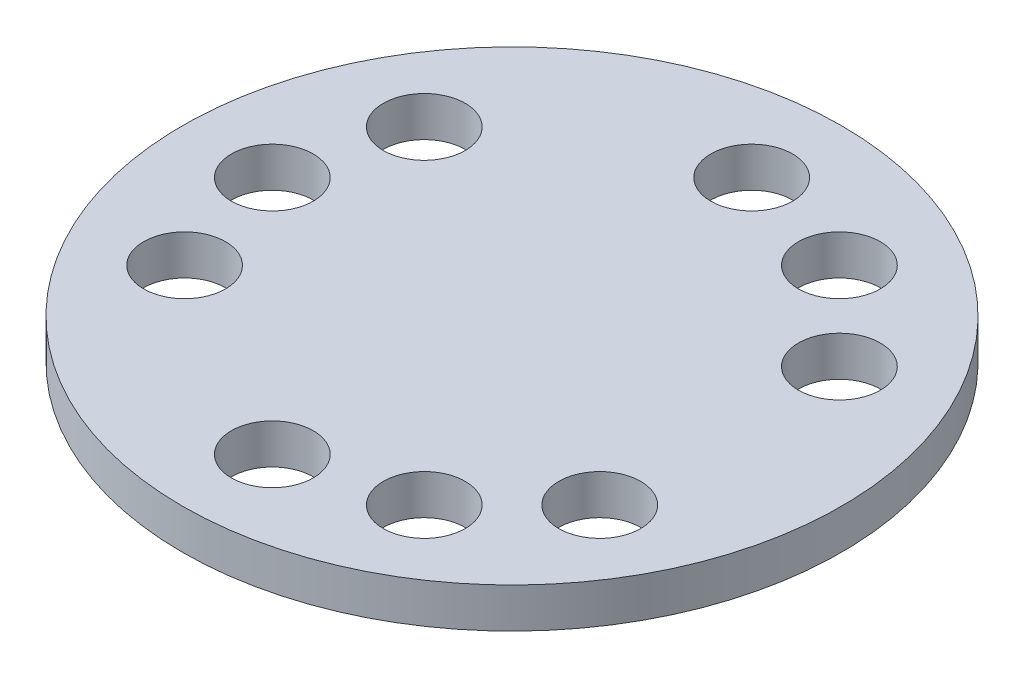
SolidWorks part; units mm, degrees
ref_plane "前视基准面" through (0, 0, 0) normal (0, 0, 1) x (1, 0, 0)
ref_plane "上视基准面" through (0, 0, 0) normal (0, 1, 0) x (1, 0, 0)
ref_plane "右视基准面" through (0, 0, 0) normal (1, 0, 0) x (0, 0, -1)
sketch "草图1" plane through (0, 0, 0) normal (0, 1, 0) x (1, 0, 0)
  line L0 (0, 0) -> (-12, 0) construction
  line L1 (0, 0) -> (6, -10.3923) construction
  line L2 (0, 0) -> (6, 10.3923) construction
  line L3 (0, 0) -> (0, 12) construction
  line L4 (0, 0) -> (10.3923, 6) construction
  line L5 (0, 0) -> (-10.3923, 6) construction
  line L6 (0, 0) -> (-10.3923, -6) construction
  line L7 (0, 0) -> (0, -12) construction
  line L8 (0, 0) -> (10.3923, -6) construction
  circle A0 centre (0, 0) radius 12 construction
  circle A1 centre (0, 0) radius 16.5
  circle A8 centre (-12, 0) radius 2.05
  circle A9 centre (6, 10.3923) radius 2.05
  circle A10 centre (6, -10.3923) radius 2.05
  circle A11 centre (0, 12) radius 2.05
  circle A12 centre (-10.3923, 6) radius 2.05
  circle A13 centre (10.3923, 6) radius 2.05
  circle A14 centre (10.3923, -6) radius 2.05
  circle A15 centre (0, -12) radius 2.05
  circle A16 centre (-10.3923, -6) radius 2.05
  dimension "D1" = 24
  dimension "D2" = 33
  dimension "D10" = 60
  dimension "D11" = 60
  dimension "D12" = 60
  dimension "D13" = 60
  dimension "D14" = 60
  dimension "D15" = 4.1
  dimension "D16" = 4.1
  dimension "D6" = 4.1
  dimension "D7" = 4.1
  dimension "D8" = 4.1
  dimension "D17" = 4.1
  dimension "D18" = 4.1
  dimension "D19" = 4.1
  dimension "D20" = 4.1
  dimension "D3" = 120
  dimension "D4" = 120
  dimension "D5" = 120
  dimension "D9" = 60
extrude "凸台-拉伸1" add sketch "草图1" along normal blind 2
